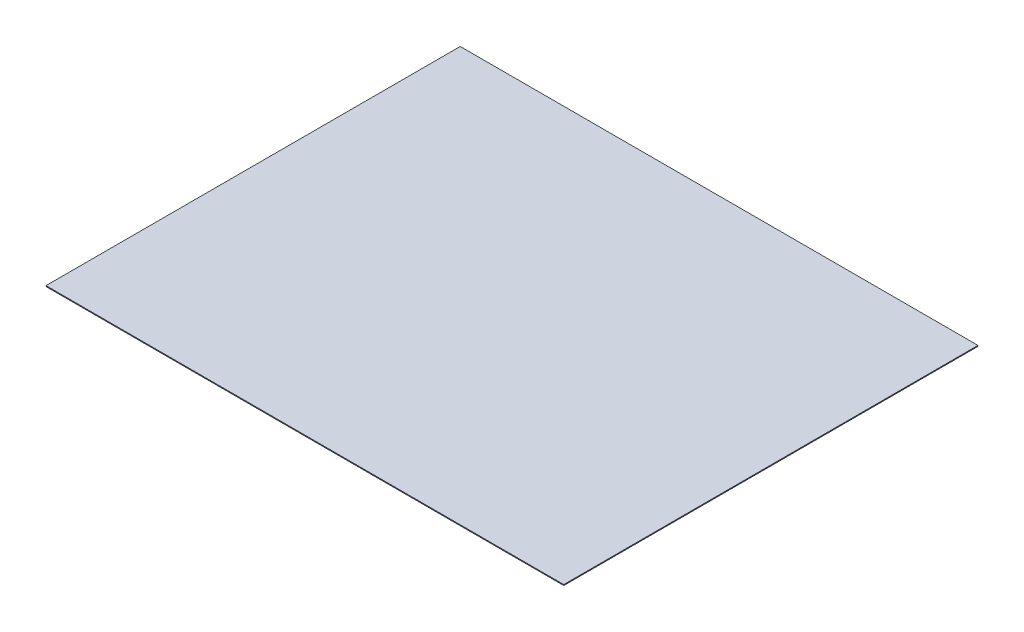
SolidWorks part; units mm, degrees
ref_plane "Front Plane" through (0, 0, 0) normal (0, 0, 1) x (1, 0, 0)
ref_plane "Top Plane" through (0, 0, 0) normal (0, 1, 0) x (1, 0, 0)
ref_plane "Right Plane" through (0, 0, 0) normal (1, 0, 0) x (0, 0, -1)
sketch "Sketch1" plane through (0, 0, 0) normal (0, 1, 0) x (1, 0, 0)
  line L1 (-762, 609.6) -> (762, 609.6)
  line L2 (-762, 609.6) -> (-762, -609.6)
  line L3 (-762, -609.6) -> (762, -609.6)
  line L4 (762, 609.6) -> (762, -609.6)
  line L5 (-762, 609.6) -> (762, -609.6) construction
  line L6 (-762, -609.6) -> (762, 609.6) construction
  point P0 (0, 0)
  dimension "D1" = 1219.2
  dimension "D2" = 1524
extrude "Boss-Extrude1" add sketch "Sketch1" along normal blind 2.54
